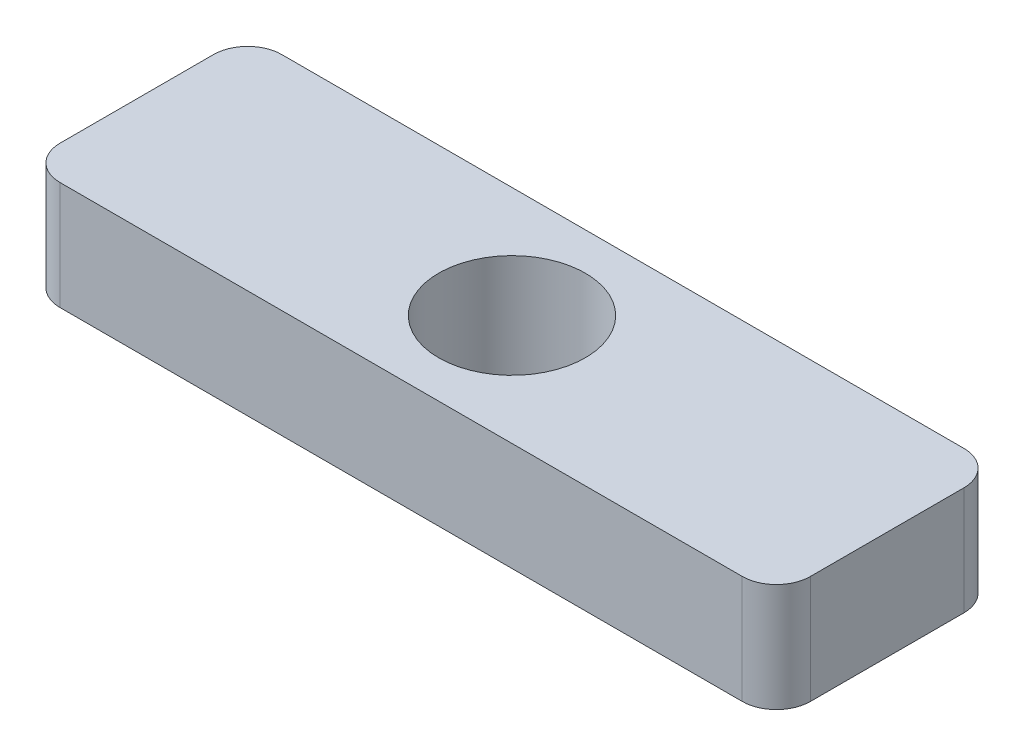
SolidWorks part; units mm, degrees
ref_plane "Front Plane" through (0, 0, 0) normal (0, 0, 1) x (1, 0, 0)
ref_plane "Top Plane" through (0, 0, 0) normal (0, 1, 0) x (1, 0, 0)
ref_plane "Right Plane" through (0, 0, 0) normal (1, 0, 0) x (0, 0, -1)
sketch "Sketch2" plane through (0, 0, 0) normal (0, 1, 0) x (1, 0, 0)
  line L1 (-11, 3.25) -> (11, 3.25)
  line L2 (-11, 3.25) -> (-11, -3.25)
  line L3 (-11, -3.25) -> (11, -3.25)
  line L4 (11, 3.25) -> (11, -3.25)
  line L5 (-11, 3.25) -> (11, -3.25) construction
  line L6 (-11, -3.25) -> (11, 3.25) construction
  point P0 (0, 0)
  dimension "D1" = 6.5
  dimension "D2" = 22
extrude "Boss-Extrude2" add sketch "Sketch2" along normal blind 3.175
sketch "Sketch3" plane through (0, 3.175, 0) normal (0, 1, 0) x (1, 0, 0)
  circle A0 centre (0, 0) radius 2.15
  dimension "D1" = 4.3
extrude "Cut-Extrude1" cut sketch "Sketch3" against normal up to surface (3.175 mm away) up to face at (0, 0, 0)
fillet "Fillet2" radius 1 4 edges at (11, 1.5875, 3.25) (11, 1.5875, -3.25) (-11, 1.5875, 3.25) (-11, 1.5875, -3.25)
